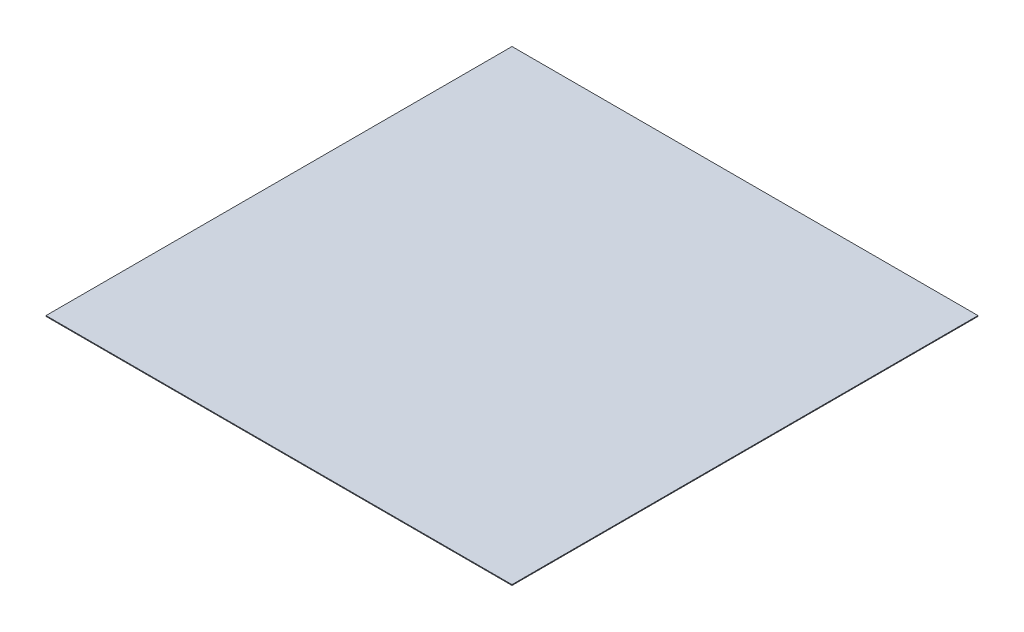
SolidWorks part; units mm, degrees
material "1100-H16 Rod (SS)"
ref_plane "Front Plane" through (0, 0, 0) normal (0, 0, 1) x (1, 0, 0)
ref_plane "Top Plane" through (0, 0, 0) normal (0, 1, 0) x (1, 0, 0)
ref_plane "Right Plane" through (0, 0, 0) normal (1, 0, 0) x (0, 0, -1)
sketch "Sketch1" plane through (0, 0, 0) normal (0, 1, 0) x (1, 0, 0)
  line L1 (-38.1, -38.1) -> (38.1, -38.1)
  line L2 (-38.1, -38.1) -> (-38.1, 38.1)
  line L3 (-38.1, 38.1) -> (38.1, 38.1)
  line L4 (38.1, -38.1) -> (38.1, 38.1)
  line L5 (-38.1, -38.1) -> (38.1, 38.1) construction
  line L6 (-38.1, 38.1) -> (38.1, -38.1) construction
  line L11 (-19.05, -19.05) -> (19.05, 19.05) construction
  line L12 (-19.05, 19.05) -> (19.05, -19.05) construction
  point P0 (0, 0)
  point P6 (0, 0)
  dimension "D1" = 76.2
  dimension "D2" = 76.2
extrude "Boss-Extrude1" add sketch "Sketch1" along normal blind 0.127
